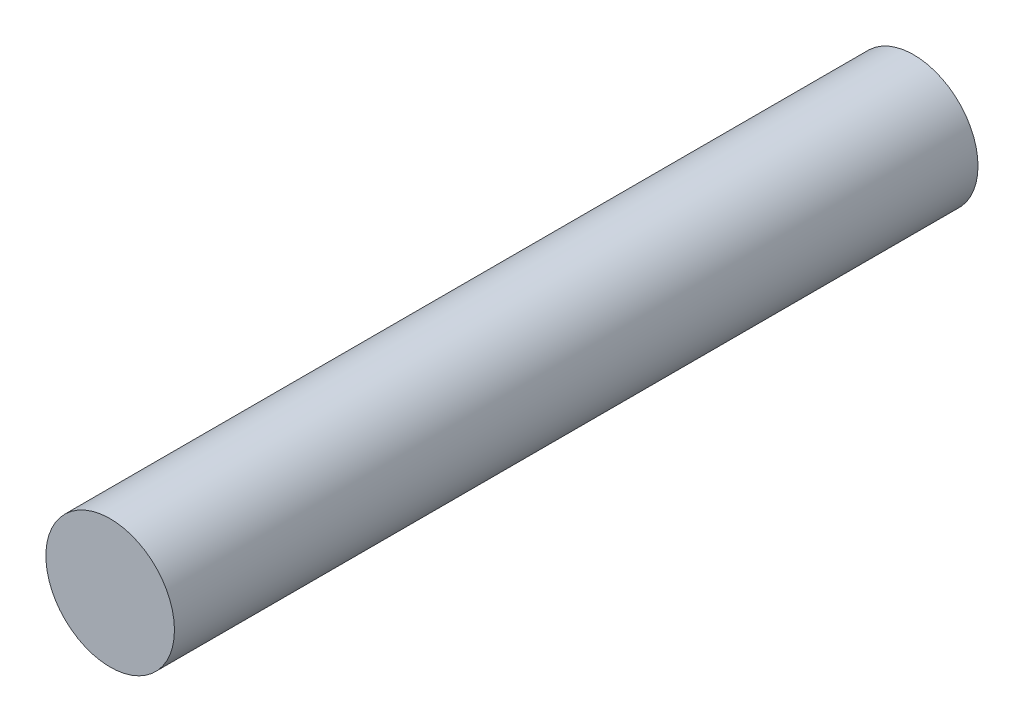
SolidWorks part; units mm, degrees
material "1023 Carbon Steel Sheet (SS)"
ref_plane "Front Plane" through (0, 0, 0) normal (0, 0, 1) x (1, 0, 0)
ref_plane "Top Plane" through (0, 0, 0) normal (0, 1, 0) x (1, 0, 0)
ref_plane "Right Plane" through (0, 0, 0) normal (1, 0, 0) x (0, 0, -1)
sketch "Sketch1" plane through (0, 0, 0) normal (0, 0, 1) x (1, 0, 0)
  circle A0 centre (0, 0) radius 8
  dimension "D1" = 16
extrude "Boss-Extrude1" add sketch "Sketch1" along normal blind 100
